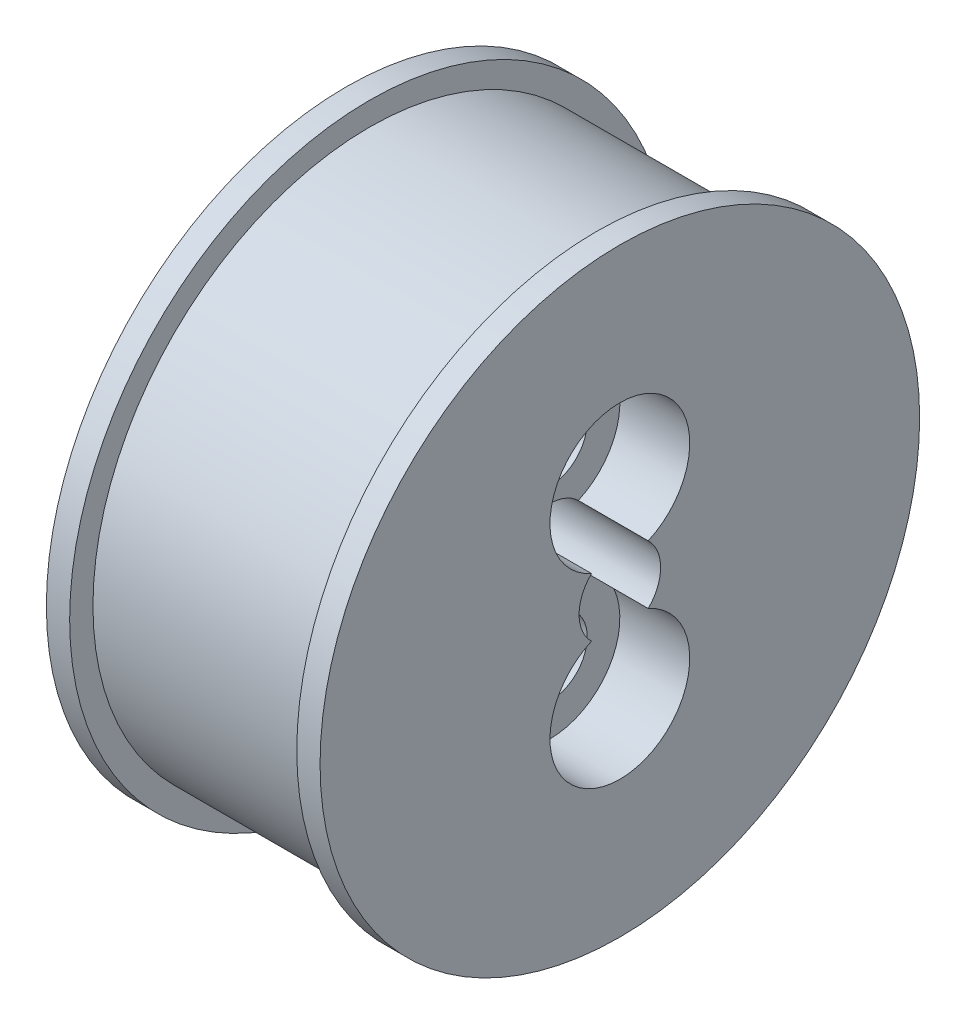
SolidWorks part; units mm, degrees
ref_plane "Front Plane" through (0, 0, 0) normal (0, 0, 1) x (1, 0, 0)
ref_plane "Top Plane" through (0, 0, 0) normal (0, 1, 0) x (1, 0, 0)
ref_plane "Right Plane" through (0, 0, 0) normal (1, 0, 0) x (0, 0, -1)
sketch "Sketch2" plane through (0, 0, 0) normal (0, 0, 1) x (1, 0, 0)
  line L0 (0, 0) -> (0, 12.87)
  line L1 (0, 12.87) -> (1, 12.87)
  line L2 (1, 12.87) -> (1, 11.87)
  line L3 (1, 11.87) -> (10.75, 11.87)
  line L4 (10.75, 11.87) -> (10.75, 12.87)
  line L5 (10.75, 12.87) -> (11.75, 12.87)
  line L6 (11.75, 12.87) -> (11.75, 0)
  line L7 (11.75, 0) -> (0, 0)
  dimension "D1" = 11.87
  dimension "D2" = 9.75
  dimension "D3" = 1
  dimension "D4" = 1
  dimension "D5" = 1
  dimension "D6" = 1
revolve "Revolve1" add sketch "Sketch2" angle 360 about L7
sketch "Sketch7" plane through (11.75, 0, 0) normal (1, 0, 0) x (0, 0, -1)
  circle A0 centre (0, 0) radius 1.75
  dimension "D1" = 3.5
extrude "Cut-Extrude1" cut sketch "Sketch7" against normal through all
hole_wizard "CBORE for M3 SHCS1" positions "Sketch10" profile "Sketch9" counterbore size "M3" standard "ANSI Metric" end condition through all
sketch "Sketch10" plane through (11.75, 0, 0) normal (1, 0, 0) x (0, 0, -1)
  line L0 (0, -12.87) -> (0, 12.87) construction
  circle A0 centre (0, 0) radius 12.87 construction
  point P0 (0, -4)
  point P2 (0, 4)
  point P12 (0, 7.3068)
  point P13 (0, -7.9112)
  point P14 (0, 0)
  dimension "D1" = 4
  dimension "D2" = 4
sketch "Sketch9" plane through (11.75, -4, 0) normal (0, 1, 0) x (0, 0, -1)
  line L0 (0, 0) -> (0, 11.75)
  line L1 (0, 11.75) -> (1.6, 11.75)
  line L3 (1.6, 11.75) -> (1.6, 3)
  line L4 (1.6, 3) -> (3, 3)
  line L5 (3, 3) -> (3, 0)
  line L7 (3, 0) -> (0, 0)
  line L11 (0, -6.35) -> (0, 107.95) construction
  dimension "Thru Hole Dia." = 3.2
  dimension "Thru Hole Depth" = 11.75
  dimension "C'Bore Dia." = 6
  dimension "C'Bore Depth" = 3
